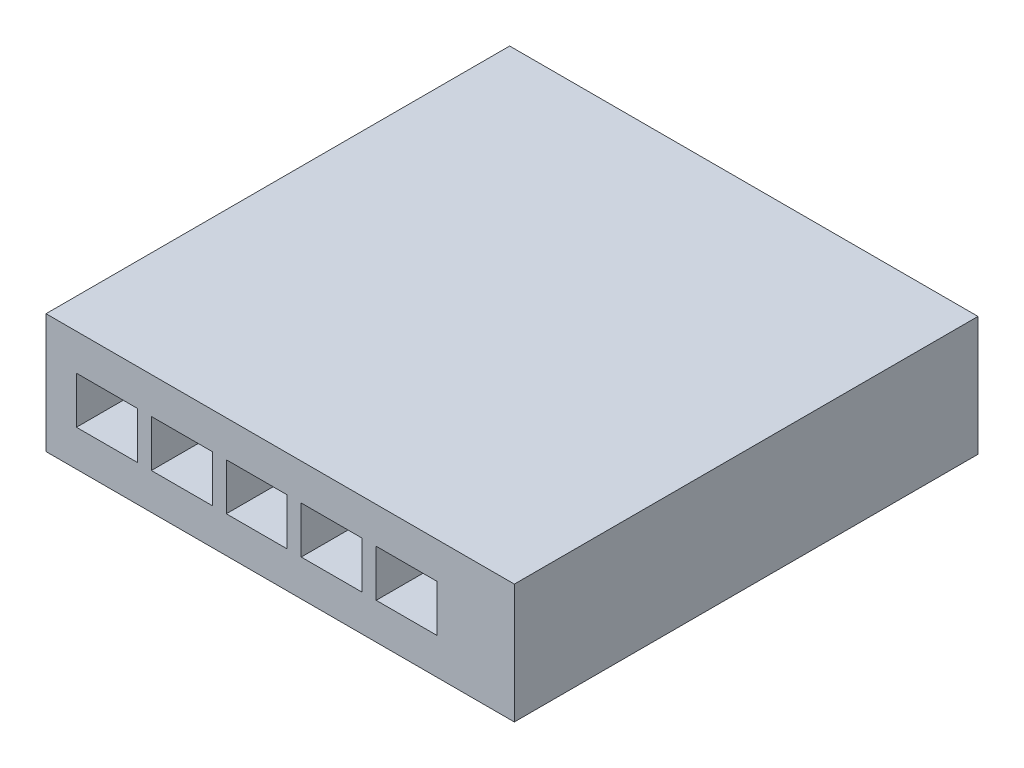
SolidWorks part; units mm, degrees
ref_plane "Front Plane" through (0, 0, 0) normal (0, 0, 1) x (1, 0, 0)
ref_plane "Top Plane" through (0, 0, 0) normal (0, 1, 0) x (1, 0, 0)
ref_plane "Right Plane" through (0, 0, 0) normal (1, 0, 0) x (0, 0, -1)
sketch "Sketch1" plane through (0, 0, 0) normal (0, 1, 0) x (1, 0, 0)
  line L1 (-50, 49.5) -> (50, 49.5)
  line L2 (-50, 49.5) -> (-50, -49.5)
  line L3 (-50, -49.5) -> (50, -49.5)
  line L4 (50, 49.5) -> (50, -49.5)
  line L5 (-50, 49.5) -> (50, -49.5) construction
  line L6 (-50, -49.5) -> (50, 49.5) construction
  point P0 (0, 0)
  dimension "D1" = 99
  dimension "D2" = 100
extrude "Boss-Extrude1" add sketch "Sketch1" along normal mid plane 25.5
sketch "Sketch2" plane through (0, 0, 49.5) normal (0, 0, 1) x (1, 0, 0)
  line L0 (-50, 0) -> (50, 0) construction
  line L1 (-50, 12.75) -> (-50, -12.75) construction
  line L2 (50, 12.75) -> (50, -12.75) construction
  line L4 (-43.5, 5) -> (-30.5, 5)
  line L5 (-43.5, 5) -> (-43.5, -5)
  line L6 (-43.5, -5) -> (-30.5, -5)
  line L7 (-30.5, 5) -> (-30.5, -5)
  line L8 (-43.5, 5) -> (-30.5, -5) construction
  line L9 (-43.5, -5) -> (-30.5, 5) construction
  point P6 (-37, 0)
  dimension "D1" = 13
  dimension "D2" = 13
  dimension "D3" = 10
extrude "Cut-Extrude1" cut sketch "Sketch2" against normal blind 20
pattern_linear "LPattern1" count 5 spacing 16 along (1, 0, 0) of "Cut-Extrude1"
sketch "Sketch3" plane through (0, 0, -49.5) normal (0, 0, -1) x (-1, 0, 0)
  line L0 (50, 0) -> (15.4561, 0) construction
  line L1 (50, 12.75) -> (50, -12.75) construction
  circle A0 centre (29, 0) radius 1.5
  dimension "D1" = 3
  dimension "D2" = 21
extrude "Cut-Extrude2" cut sketch "Sketch3" against normal blind 10
